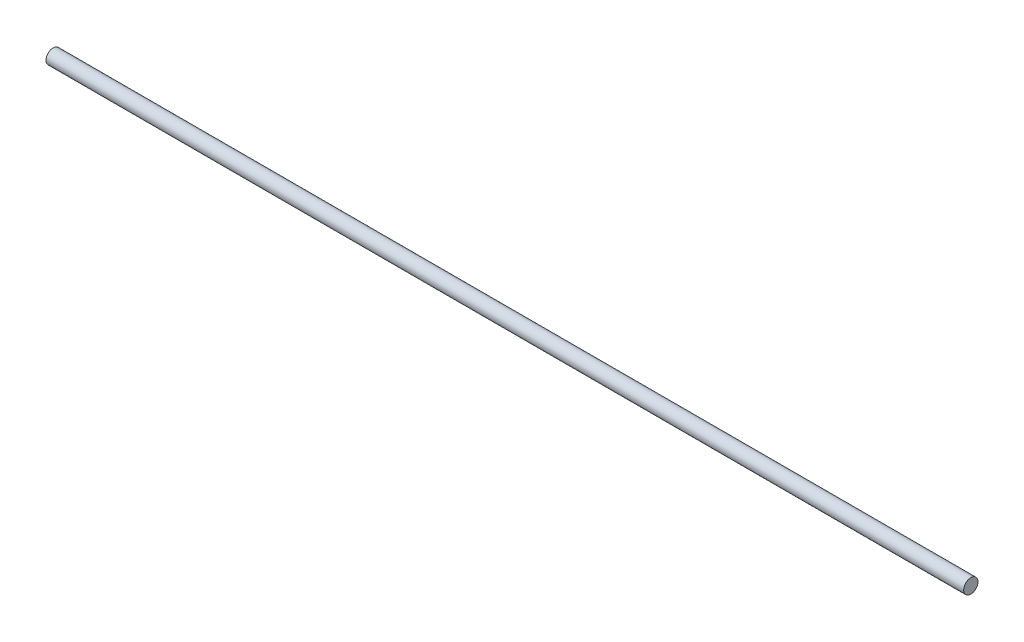
SolidWorks part; units mm, degrees
material "Stainless Steel (ferritic)"
ref_plane "Front Plane" through (0, 0, 0) normal (0, 0, 1) x (1, 0, 0)
ref_plane "Top Plane" through (0, 0, 0) normal (0, 1, 0) x (1, 0, 0)
ref_plane "Right Plane" through (0, 0, 0) normal (1, 0, 0) x (0, 0, -1)
sketch "Sketch1" plane through (0, 0, 0) normal (1, 0, 0) x (0, 0, -1)
  circle A0 centre (0, 0) radius 1.9844
  dimension "D1" = 3.9688
extrude "Boss-Extrude1" add sketch "Sketch1" along normal mid plane 254
